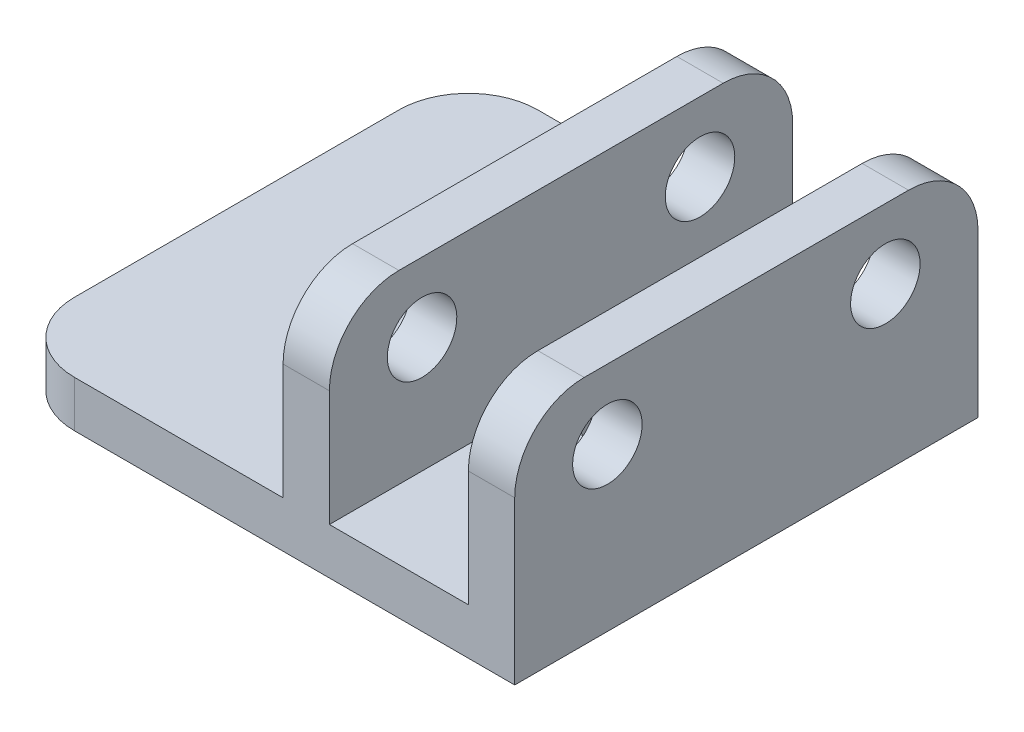
SolidWorks part; units mm, degrees
ref_plane "Front Plane" through (0, 0, 0) normal (0, 0, 1) x (1, 0, 0)
ref_plane "Top Plane" through (0, 0, 0) normal (0, 1, 0) x (1, 0, 0)
ref_plane "Right Plane" through (0, 0, 0) normal (1, 0, 0) x (0, 0, -1)
sketch "Sketch1" plane through (0, 0, 0) normal (0, 0, 1) x (1, 0, 0)
  line L0 (0, 0) -> (0, 4) construction
  line L1 (5, 0) -> (-17, 0)
  line L2 (-17, 0) -> (-17, 2)
  line L3 (-17, 2) -> (-5, 2)
  line L4 (-5, 2) -> (-5, 10)
  line L5 (-5, 10) -> (-3, 10)
  line L6 (-3, 10) -> (-3, 2)
  line L7 (-3, 2) -> (3, 2)
  line L8 (3, 10) -> (3, 2)
  line L9 (5, 10) -> (3, 10)
  line L11 (5, 10) -> (5, 0)
  point P11 (0, 2)
  point P13 (0, 0)
  point P14 (0, 0)
  point P16 (0, 0)
  dimension "D1" = 3
  dimension "D2" = 17
  dimension "D3" = 12
  dimension "D4" = 2
  dimension "D5" = 8
extrude "Boss-Extrude1" add sketch "Sketch1" along normal blind 20
fillet "Fillet1" radius 3 6 edges at (-4, 10, 0) (4, 10, 0) (-17, 1, 0) (-17, 1, 20) (4, 10, 20) (-4, 10, 20)
sketch "Sketch2" plane through (-5, 0, 0) normal (-1, 0, 0) x (0, 0, 1)
  line L0 (10, 10) -> (10, 2) construction
  line L1 (17, 10) -> (3, 10) construction
  line L2 (20, 2) -> (0, 2) construction
  circle A0 centre (16, 7) radius 1.5
  circle A1 centre (4, 7) radius 1.5
  point P10 (17.7993, 7.5619)
  dimension "D3" = 3
  dimension "D1" = 6
  dimension "D2" = 3
extrude "Cut-Extrude1" cut sketch "Sketch2" against normal blind 20
sketch "Sketch3" plane through (0, 2, 0) normal (0, 1, 0) x (1, 0, 0)
  line L0 (-3, -10) -> (3, -10) construction
  line L1 (-3, -20) -> (-3, 0) construction
  line L2 (3, -20) -> (3, 0) construction
  circle A0 centre (0, -10) radius 1.5
  dimension "D1" = 3
extrude "Cut-Extrude2" cut sketch "Sketch3" against normal blind 20
